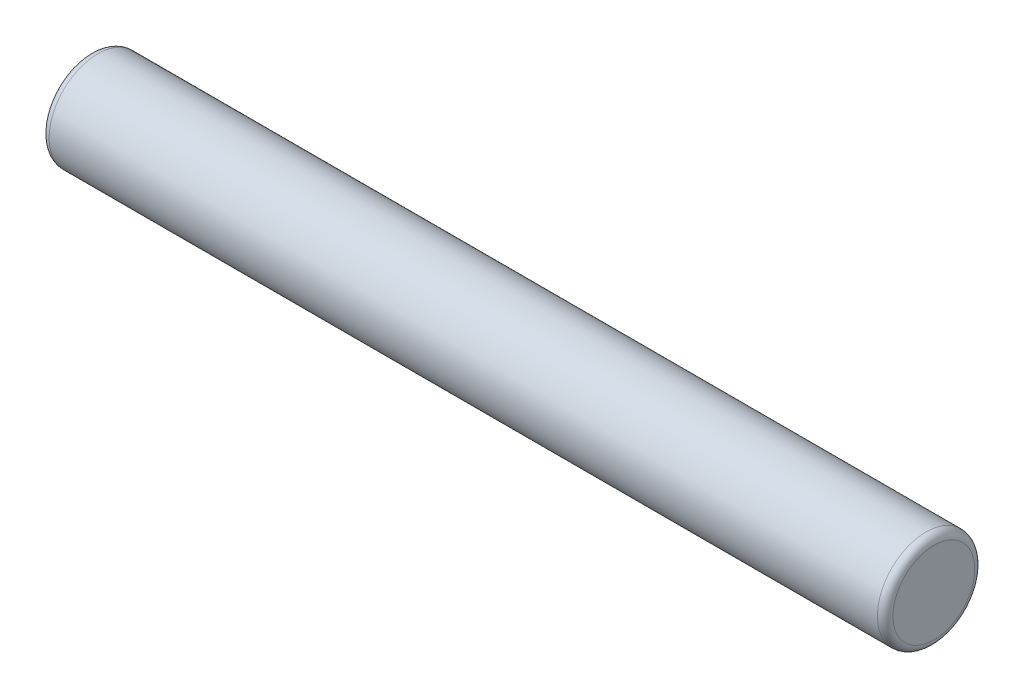
SolidWorks part; units mm, degrees
material "Alloy Steel (SS)"
ref_plane "Front Plane" through (0, 0, 0) normal (0, 0, 1) x (1, 0, 0)
ref_plane "Top Plane" through (0, 0, 0) normal (0, 1, 0) x (1, 0, 0)
ref_plane "Right Plane" through (0, 0, 0) normal (1, 0, 0) x (0, 0, -1)
sketch "Sketch1" plane through (0, 0, 0) normal (1, 0, 0) x (0, 0, -1)
  circle A0 centre (0, 0) radius 6.35
  dimension "D1" = 12.7
extrude "Boss-Extrude1" add sketch "Sketch1" along normal blind 110
fillet "Fillet1" radius 1.016 2 edges at (110, 0, -6.35) (0, 0, -6.35)
